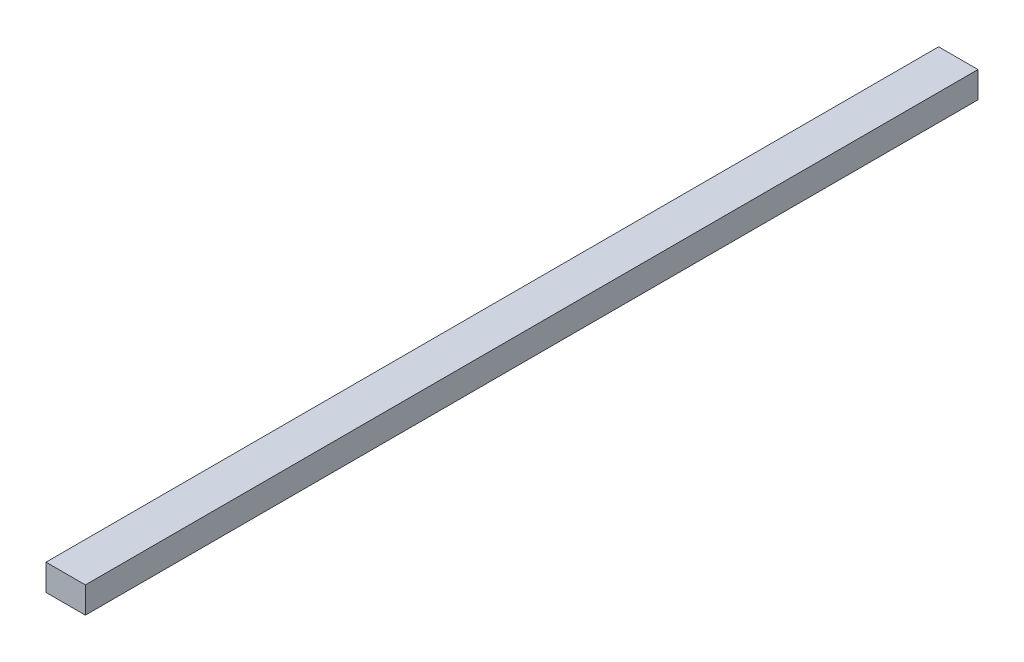
SolidWorks part; units mm, degrees
ref_plane "Front Plane" through (0, 0, 0) normal (0, 0, 1) x (1, 0, 0)
ref_plane "Top Plane" through (0, 0, 0) normal (0, 1, 0) x (1, 0, 0)
ref_plane "Right Plane" through (0, 0, 0) normal (1, 0, 0) x (0, 0, -1)
other "Configuration Table"
sketch "Sketch1" plane through (0, 0, 0) normal (0, 0, 1) x (1, 0, 0)
  line L1 (-65, 0) -> (-35, 0)
  line L2 (-65, 0) -> (-65, 20)
  line L3 (-65, 20) -> (-35, 20)
  line L4 (-35, 0) -> (-35, 20)
extrude "KAP_kizak_sol_30x20_1" add sketch "Sketch1" against normal blind 680 from offset 20 separate body
